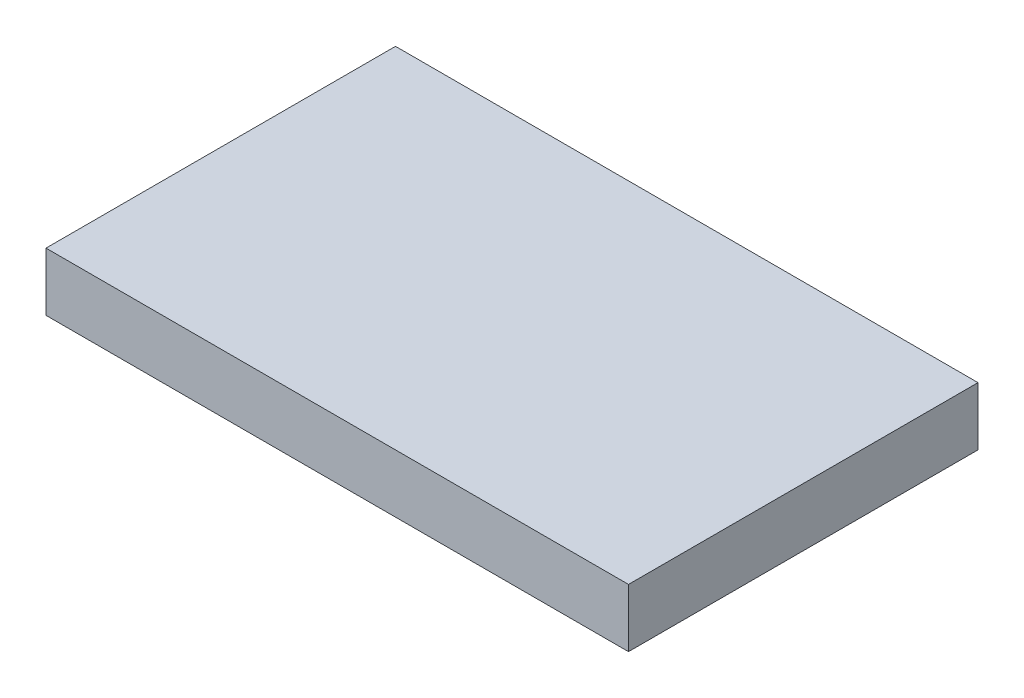
SolidWorks part; units mm, degrees
ref_plane "Front Plane" through (0, 0, 0) normal (0, 0, 1) x (1, 0, 0)
ref_plane "Top Plane" through (0, 0, 0) normal (0, 1, 0) x (1, 0, 0)
ref_plane "Right Plane" through (0, 0, 0) normal (1, 0, 0) x (0, 0, -1)
sketch "Sketch1" plane through (0, 0, 0) normal (0, 1, 0) x (1, 0, 0)
  line L1 (0, 0) -> (20, 0)
  line L2 (0, 0) -> (0, -12)
  line L3 (0, -12) -> (20, -12)
  line L4 (20, 0) -> (20, -12)
  dimension "D1" = 20
  dimension "D2" = 12
extrude "Boss-Extrude2" add sketch "Sketch1" along normal blind 2
